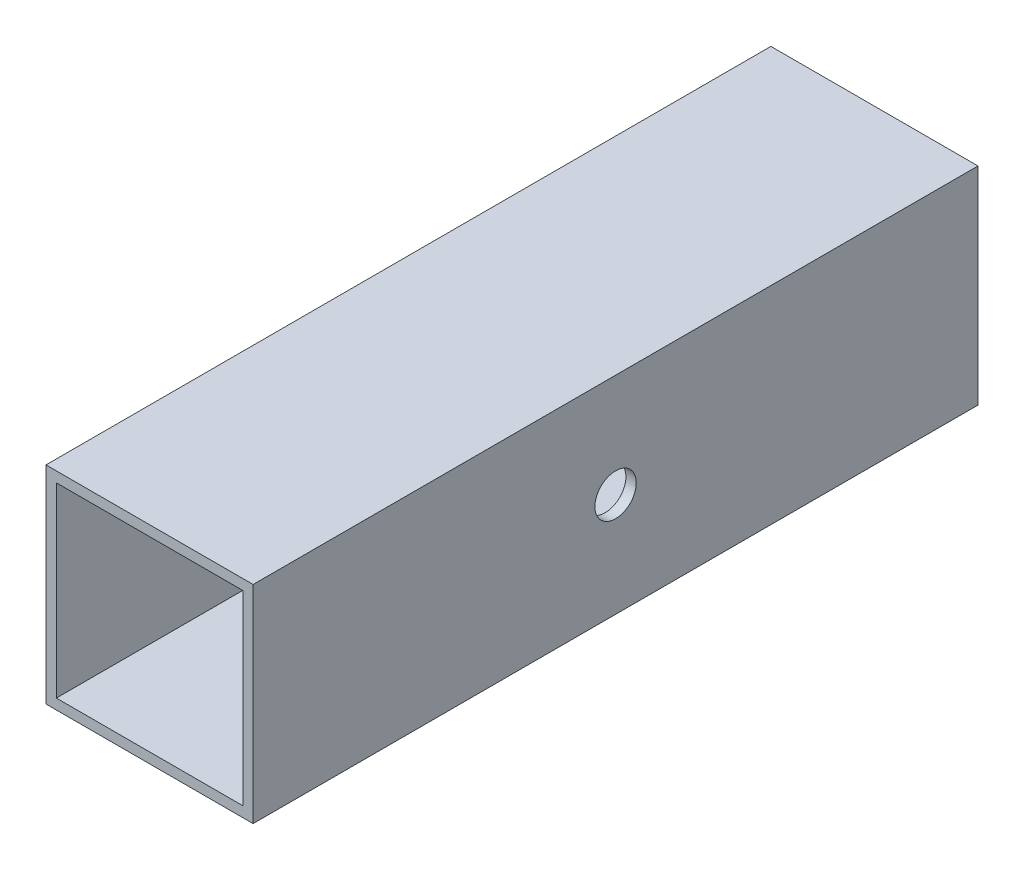
SolidWorks part; units mm, degrees
ref_plane "Plan de face" through (0, 0, 0) normal (0, 0, 1) x (1, 0, 0)
ref_plane "Plan de dessus" through (0, 0, 0) normal (0, 1, 0) x (1, 0, 0)
ref_plane "Plan de droite" through (0, 0, 0) normal (1, 0, 0) x (0, 0, -1)
sketch "Esquisse1" plane through (0, 0, 0) normal (0, 0, 1) x (1, 0, 0)
  line L0 (9, 9) -> (-9, 9)
  line L1 (10, -10) -> (-10, -10)
  line L2 (10, -10) -> (10, 10)
  line L3 (10, 10) -> (-10, 10)
  line L4 (-10, -10) -> (-10, 10)
  line L5 (10, -10) -> (-10, 10) construction
  line L6 (10, 10) -> (-10, -10) construction
  line L7 (-9, -9) -> (-9, 9)
  line L8 (9, -9) -> (-9, -9)
  line L9 (9, -9) -> (9, 9)
  point P0 (0, 0)
  dimension "D1" = 20
  dimension "D2" = 20
  dimension "D3" = 1
extrude "Boss.-Extru.1" add sketch "Esquisse1" along normal blind 70
sketch "Esquisse2" plane through (10, 0, 0) normal (1, 0, 0) x (0, 0, -1)
  line L0 (-70, 10) -> (0, 10) construction
  circle A0 centre (-35, 0) radius 2
  point P2 (0, 0)
  point P6 (-35, 10)
  dimension "D1" = 4
extrude "Enlèv. mat.-Extru.1" cut sketch "Esquisse2" against normal blind 40
